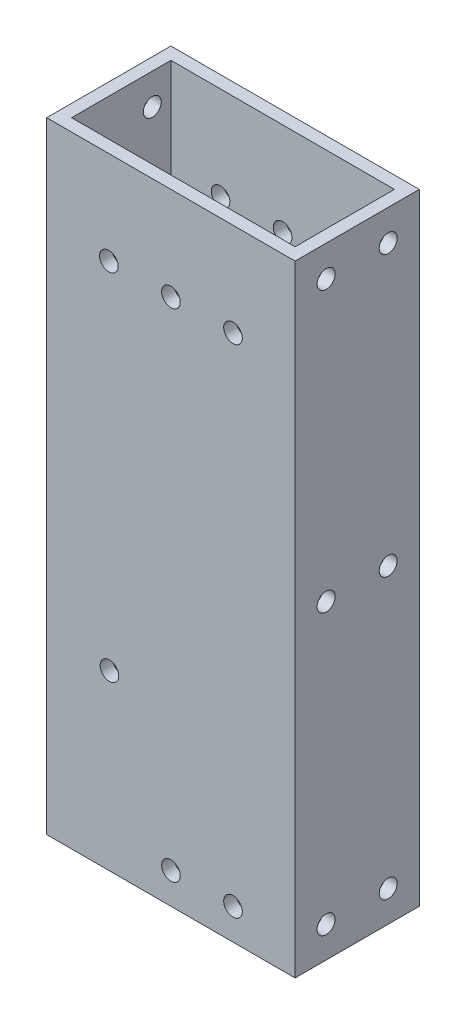
SolidWorks part; units mm, degrees
ref_plane "前视基准面" through (0, 0, 0) normal (0, 0, 1) x (1, 0, 0)
ref_plane "上视基准面" through (0, 0, 0) normal (0, 1, 0) x (1, 0, 0)
ref_plane "右视基准面" through (0, 0, 0) normal (1, 0, 0) x (0, 0, -1)
sketch "草图1" plane through (0, 0, 0) normal (0, 1, 0) x (1, 0, 0)
  line L1 (-20, 10) -> (20, 10)
  line L2 (-20, 10) -> (-20, -10)
  line L3 (-20, -10) -> (20, -10)
  line L4 (20, 10) -> (20, -10)
  line L5 (-20, 10) -> (20, -10) construction
  line L6 (-20, -10) -> (20, 10) construction
  line L7 (-18, 8) -> (18, 8)
  line L8 (-18, 8) -> (-18, -8)
  line L9 (-18, -8) -> (18, -8)
  line L10 (18, 8) -> (18, -8)
  line L11 (-18, 8) -> (18, -8) construction
  line L12 (-18, -8) -> (18, 8) construction
  point P0 (0, 0)
  point P6 (0, 0)
  dimension "D1" = 40
  dimension "D2" = 20
  dimension "D3" = 2
  dimension "D4" = 2
extrude "凸台-拉伸1" add sketch "草图1" along normal mid plane 100
sketch "草图2" plane through (20, 0, 0) normal (1, 0, 0) x (0, 0, -1)
  line L0 (-10, 50) -> (10, 50) construction
  line L1 (-5, 45) -> (5, 45) construction
  line L2 (-5, 45) -> (-5, -45) construction
  line L3 (-5, -45) -> (5, -45) construction
  line L4 (5, 45) -> (5, -45) construction
  line L5 (-5, 45) -> (5, -45) construction
  line L6 (-5, -45) -> (5, 45) construction
  line L7 (10, 50) -> (10, -50) construction
  line L8 (-10, 50) -> (-10, -50) construction
  line L9 (-10, -50) -> (10, -50) construction
  circle A0 centre (5, 45) radius 1.45
  circle A1 centre (-5, 45) radius 1.45
  circle A2 centre (5, 0) radius 1.45
  circle A4 centre (-5, 0) radius 1.45
  circle A5 centre (5, -45) radius 1.45
  circle A6 centre (-5, -45) radius 1.45
  point P0 (0, 0)
  dimension "D5" = 2.9
  dimension "D1" = 5
  dimension "D2" = 5
  dimension "D3" = 5
  dimension "D4" = 5
extrude "切除-拉伸1" cut sketch "草图2" against normal through all
sketch "草图3" plane through (0, 0, -10) normal (0, 0, -1) x (-1, 0, 0)
  circle A0 centre (10, 35) radius 1.5
  circle A1 centre (10, 35) radius 1.5 construction
  circle A2 centre (0, 35) radius 1.5
  circle A3 centre (-10, 35) radius 1.5
extrude "切除-拉伸2" cut sketch "草图3" against normal through all
sketch "草图4" plane through (0, 0, -10) normal (0, 0, -1) x (-1, 0, 0)
  line L0 (9.9, -20.85) -> (9.9, -23.325) construction
  circle A1 centre (0, -45) radius 1.5
  circle A2 centre (-10, -45) radius 1.5
  circle A3 centre (9.9, -22.0875) radius 1.5
  dimension "D1" = 3
extrude "切除-拉伸3" cut sketch "草图4" against normal through all
